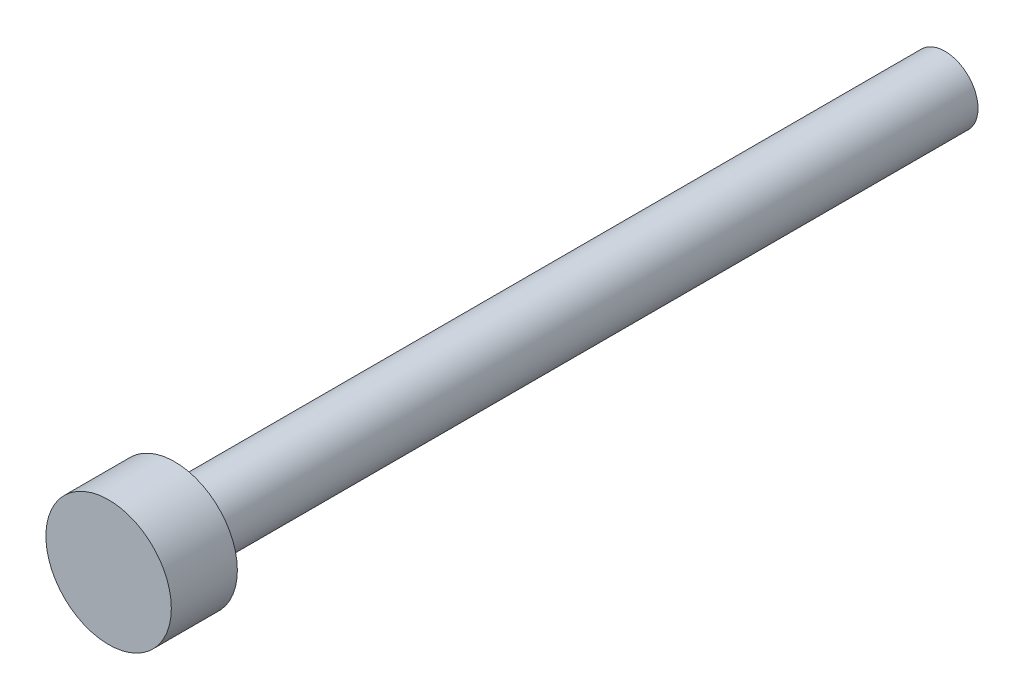
SolidWorks part; units mm, degrees
ref_plane "Front Plane" through (0, 0, 0) normal (0, 0, 1) x (1, 0, 0)
ref_plane "Top Plane" through (0, 0, 0) normal (0, 1, 0) x (1, 0, 0)
ref_plane "Right Plane" through (0, 0, 0) normal (1, 0, 0) x (0, 0, -1)
sketch "Sketch1" plane through (0, 0, 0) normal (0, 0, 1) x (1, 0, 0)
  circle A0 centre (0, 0) radius 1.5
  dimension "D1" = 3
extrude "Boss-Extrude1" add sketch "Sketch1" along normal blind 35
sketch "Sketch2" plane through (0, 0, 35) normal (0, 0, 1) x (1, 0, 0)
  circle A0 centre (0, 0) radius 2.85
  dimension "D1" = 5.7
extrude "Boss-Extrude2" add sketch "Sketch2" along normal blind 3
